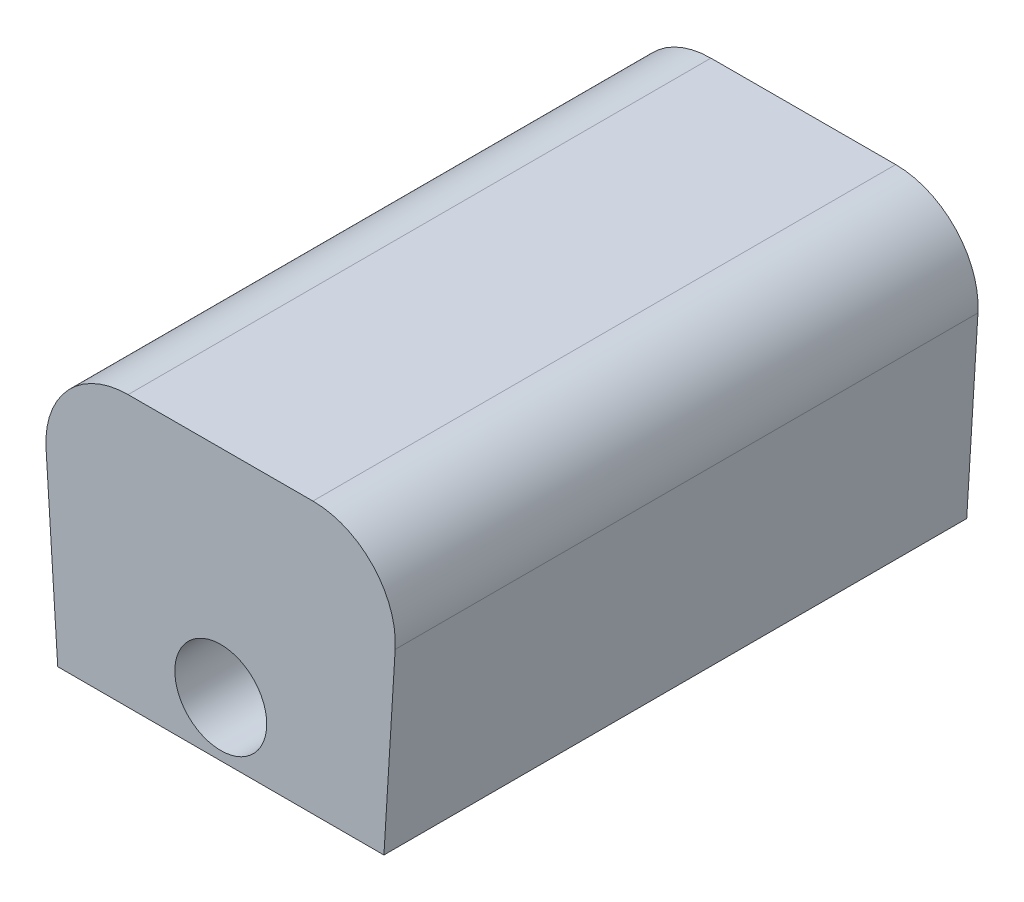
SolidWorks part; units mm, degrees
ref_plane "Front Plane" through (0, 0, 0) normal (0, 0, 1) x (1, 0, 0)
ref_plane "Top Plane" through (0, 0, 0) normal (0, 1, 0) x (1, 0, 0)
ref_plane "Right Plane" through (0, 0, 0) normal (1, 0, 0) x (0, 0, -1)
sketch "Sketch1" plane through (0, 0, 0) normal (0, 0, 1) x (1, 0, 0)
  line L0 (-14.2437, 12.8838) -> (-12.5485, 40.5595)
  line L1 (-16.3561, 44.6024) -> (-24.9102, 44.5918)
  line L2 (-28.7077, 40.5394) -> (-26.9437, 12.868)
  circle A0 centre (-20.6207, 34.5961) radius 2.127
  arc A1 (-26.9437, 12.868) -> (-14.2437, 12.8838) centre (-20.5939, 13.0075) ccw
  arc A2 (-12.5485, 40.5595) -> (-16.3561, 44.6024) centre (-16.3514, 40.7924) ccw
  arc A3 (-24.9102, 44.5918) -> (-28.7077, 40.5394) centre (-24.9054, 40.7818) ccw
  circle A4 centre (-20.5923, 11.7361) radius 2.127
extrude "Boss-Extrude1" add sketch "Sketch1" along normal blind 26.9748
sketch "Sketch2" plane through (0, 0, 26.9748) normal (0, 0, 1) x (1, 0, 0)
  line L1 (-34.6352, 1.2336) -> (-8.1994, 1.2336)
  line L2 (-34.6352, 1.2336) -> (-34.6352, 32.0561)
  line L3 (-34.6352, 32.0561) -> (-8.1994, 32.0561)
  line L4 (-8.1994, 1.2336) -> (-8.1994, 32.0561)
  circle A0 centre (-20.6207, 34.5961) radius 2.127 construction
  dimension "D1" = 2.54
extrude "Cut-Extrude1" cut sketch "Sketch2" against normal blind 26.9748
